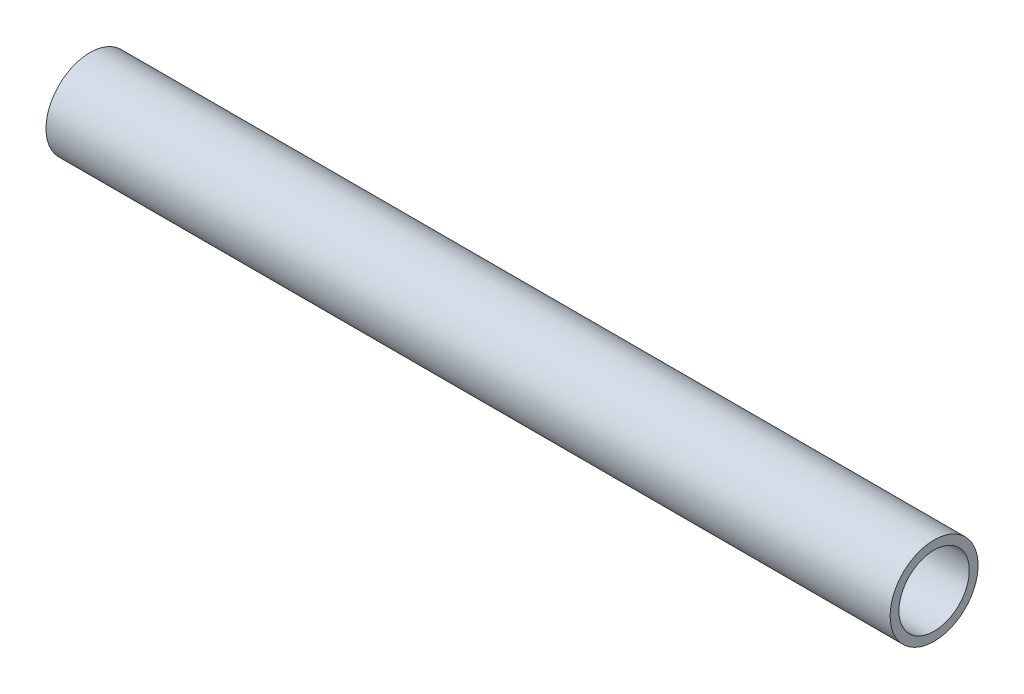
SolidWorks part; units mm, degrees
material "Acrylic (Medium-high impact)"
ref_plane "Front" through (0, 0, 0) normal (0, 0, 1) x (1, 0, 0)
ref_plane "Top" through (0, 0, 0) normal (0, 1, 0) x (1, 0, 0)
ref_plane "Right" through (0, 0, 0) normal (1, 0, 0) x (0, 0, -1)
sketch "Sketch1" plane through (0, 0, 0) normal (1, 0, 0) x (0, 0, -1)
  circle A0 centre (0, 0) radius 15.875
  circle A1 centre (0, 0) radius 12.7
  point P4 (15.875, 0)
  point P5 (12.7, 0)
  dimension "OD" = 31.75
  dimension "ID" = 25.4
  dimension "Wall" = 3.175
extrude "Extrude1" add sketch "Sketch1" along normal mid plane 304.8
